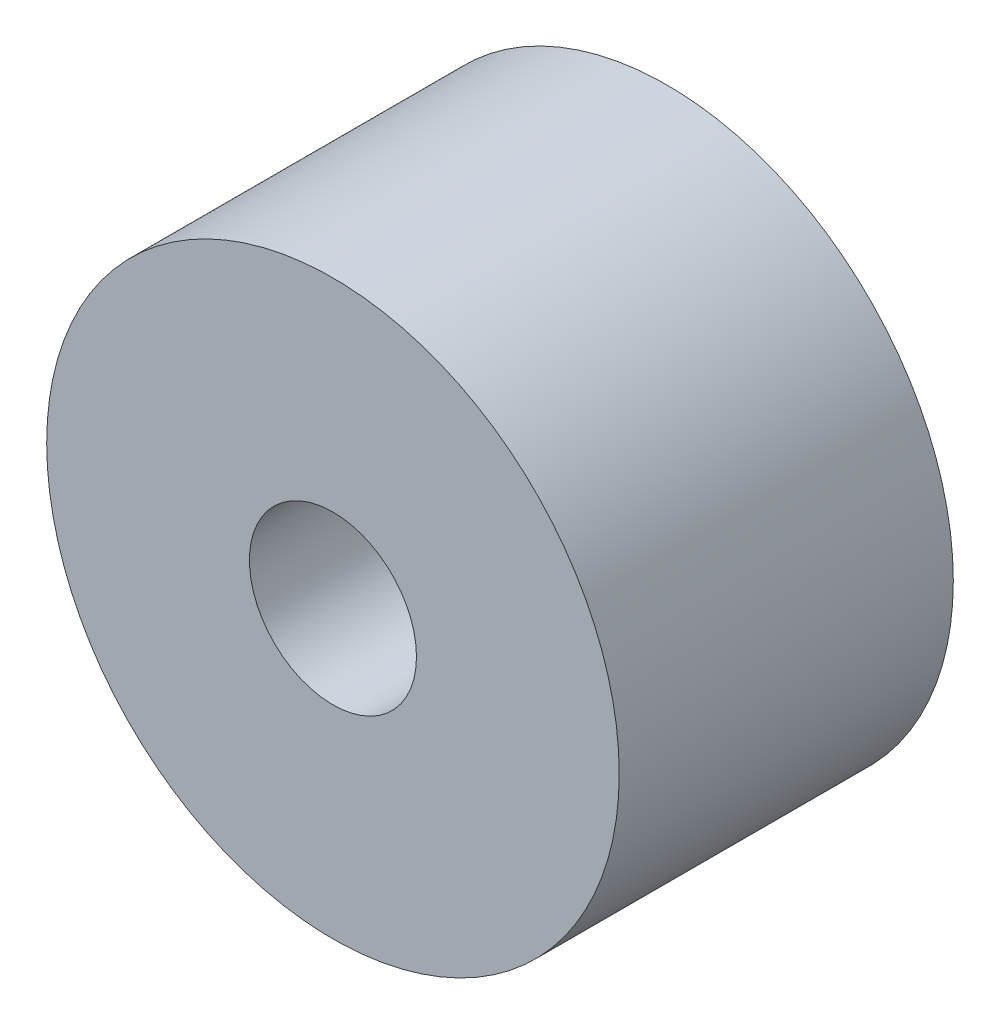
SolidWorks part; units mm, degrees
ref_plane "Front Plane" through (0, 0, 0) normal (0, 0, 1) x (1, 0, 0)
ref_plane "Top Plane" through (0, 0, 0) normal (0, 1, 0) x (1, 0, 0)
ref_plane "Right Plane" through (0, 0, 0) normal (1, 0, 0) x (0, 0, -1)
sketch "Sketch1" plane through (0, 0, 0) normal (0, 0, 1) x (1, 0, 0)
  circle A0 centre (0, 0) radius 10.8824
  circle A1 centre (0, 0) radius 3.175
  dimension "D1" = 21.7648
  dimension "D2" = 6.35
extrude "Boss-Extrude1" add sketch "Sketch1" along normal blind 12.7
